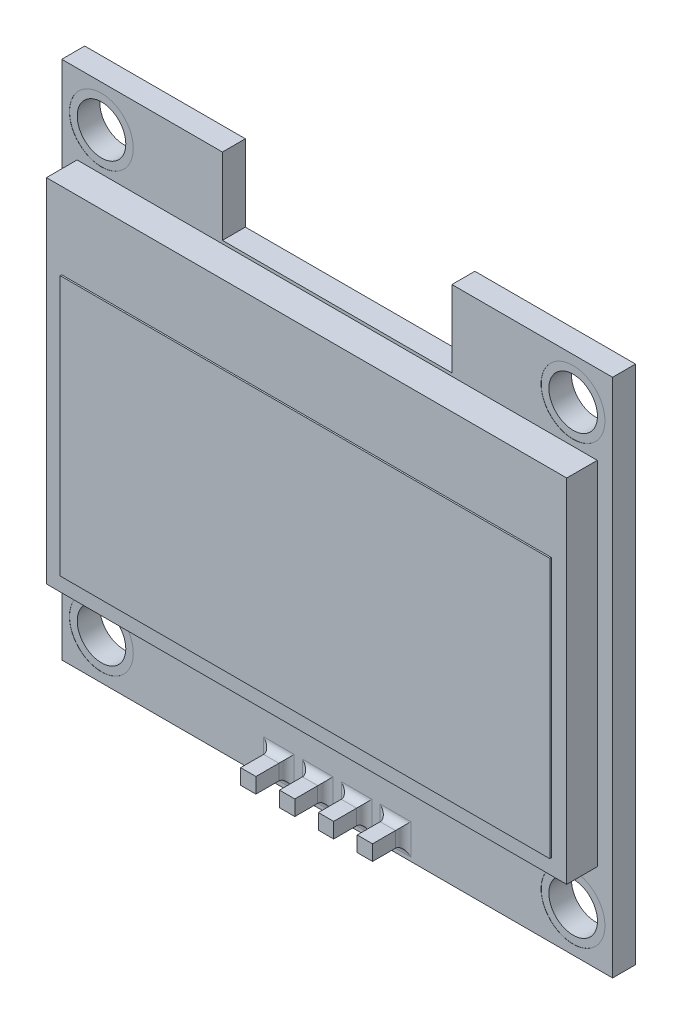
SolidWorks part; units mm, degrees
ref_plane "Alzado" through (0, 0, 0) normal (0, 0, 1) x (1, 0, 0)
ref_plane "Planta" through (0, 0, 0) normal (0, 1, 0) x (1, 0, 0)
ref_plane "Vista lateral" through (0, 0, 0) normal (1, 0, 0) x (0, 0, -1)
sketch "Croquis1" plane through (0, 0, 0) normal (0, 0, 1) x (1, 0, 0)
  line L1 (-18, 17) -> (18, 17)
  line L2 (-18, 17) -> (-18, -17)
  line L3 (-18, -17) -> (18, -17)
  line L4 (18, 17) -> (18, -17)
  line L5 (-18, 17) -> (18, -17) construction
  line L6 (-18, -17) -> (18, 17) construction
  point P0 (0, 0)
  dimension "D1" = 36
  dimension "D2" = 34
extrude "Saliente-Extruir1" add sketch "Croquis1" along normal blind 1.5
sketch "Croquis2" plane through (0, 0, 1.5) normal (0, 0, 1) x (1, 0, 0)
  line L0 (18, 17) -> (-18, 17) construction
  line L1 (-7.5, 17) -> (7.5, 17)
  line L2 (-7.5, 17) -> (-7.5, 12)
  line L3 (-7.5, 12) -> (7.5, 12)
  line L4 (7.5, 17) -> (7.5, 12)
  point P6 (0, 12)
  point P7 (0, 17)
  dimension "D1" = 15
  dimension "D2" = 5
extrude "Cortar-Extruir1" cut sketch "Croquis2" against normal blind 1.5
sketch "Croquis3" plane through (0, 0, 1.5) normal (0, 0, 1) x (1, 0, 0)
  line L0 (15.4125, 14.2875) -> (15.4125, -14.2875) construction
  line L1 (18, -17) -> (18, 17) construction
  line L2 (-15.4125, -14.2875) -> (15.4125, -14.2875) construction
  line L3 (-18, -17) -> (18, -17) construction
  circle A0 centre (-15.4125, 14.2875) radius 1.5875
  circle A1 centre (15.4125, 14.2875) radius 1.5875
  circle A2 centre (15.4125, -14.2875) radius 1.5875
  circle A3 centre (-15.4125, -14.2875) radius 1.5875
  point P8 (15.4125, 15.875)
  point P9 (17, 14.2875)
  point P10 (15.4125, -15.875)
  point P11 (-17, 14.2875)
  point P12 (15.4125, 0)
  point P13 (18, 0)
  point P14 (0, -14.2875)
  point P17 (0, -17)
  dimension "D1" = 3.175
  dimension "D2" = 31.75
  dimension "D3" = 34
extrude "Cortar-Extruir2" cut sketch "Croquis3" against normal blind 2.54
sketch "Croquis4" plane through (0, 0, 1.5) normal (0, 0, 1) x (1, 0, 0)
  line L0 (-18, -17) -> (18, -17) construction
  line L1 (-17, 11.8) -> (17, 11.8)
  line L2 (-17, 11.8) -> (-17, -11.2)
  line L3 (-17, -11.2) -> (17, -11.2)
  line L4 (17, 11.8) -> (17, -11.2)
  point P6 (0, -11.2)
  dimension "D1" = 34
  dimension "D2" = 23
  dimension "D3" = 5.8
extrude "Saliente-Extruir2" add sketch "Croquis4" along normal blind 2
sketch "Croquis5" plane through (0, 0, 3.5) normal (0, 0, 1) x (1, 0, 0)
  line L0 (-17, -11.2) -> (17, -11.2) construction
  line L1 (16, -10.2) -> (-16, -10.2)
  line L2 (16, -10.2) -> (16, 6.8)
  line L3 (16, 6.8) -> (-16, 6.8)
  line L4 (-16, -10.2) -> (-16, 6.8)
  line L5 (17, -11.2) -> (17, 11.8) construction
  line L6 (-17, 11.8) -> (-17, -11.2) construction
  line L7 (17, 11.8) -> (-17, 11.8) construction
  dimension "D1" = 1
  dimension "D2" = 1
  dimension "D3" = 1
  dimension "D4" = 5
extrude "Saliente-Extruir5" add sketch "Croquis5" along normal blind 0.1
sketch "Croquis15" plane through (0, 0, 1.5) normal (0, 0, 1) x (1, 0, 0)
  line L0 (-18, -17) -> (18, -17) construction
  line L1 (1.77, -16.25) -> (0.77, -16.25)
  line L2 (4.31, -16.25) -> (3.31, -16.25)
  line L3 (4.31, -16.25) -> (4.31, -15.25)
  line L4 (4.31, -15.25) -> (3.31, -15.25)
  line L5 (3.31, -16.25) -> (3.31, -15.25)
  line L6 (4.31, -16.25) -> (3.31, -15.25) construction
  line L7 (4.31, -15.25) -> (3.31, -16.25) construction
  line L8 (1.77, -16.25) -> (1.77, -15.25)
  line L9 (1.77, -15.25) -> (0.77, -15.25)
  line L10 (0.77, -16.25) -> (0.77, -15.25)
  line L11 (1.77, -16.25) -> (0.77, -15.25) construction
  line L12 (1.77, -15.25) -> (0.77, -16.25) construction
  line L13 (-0.77, -16.25) -> (-1.77, -16.25)
  line L14 (-0.77, -16.25) -> (-0.77, -15.25)
  line L15 (-0.77, -15.25) -> (-1.77, -15.25)
  line L16 (-1.77, -16.25) -> (-1.77, -15.25)
  line L17 (-0.77, -16.25) -> (-1.77, -15.25) construction
  line L18 (-0.77, -15.25) -> (-1.77, -16.25) construction
  line L19 (-3.31, -16.25) -> (-4.31, -16.25)
  line L20 (-3.31, -16.25) -> (-3.31, -15.25)
  line L21 (-3.31, -15.25) -> (-4.31, -15.25)
  line L22 (-4.31, -16.25) -> (-4.31, -15.25)
  line L23 (-3.31, -16.25) -> (-4.31, -15.25) construction
  line L24 (-3.31, -15.25) -> (-4.31, -16.25) construction
  line L25 (3.81, -15.75) -> (1.27, -15.75) construction
  line L26 (0.77, -15.75) -> (-0.77, -15.75) construction
  point P0 (3.81, -15.75)
  point P3 (3.81, -15.75)
  point P10 (1.27, -15.75)
  point P11 (1.27, -15.75)
  point P16 (-1.27, -15.75)
  point P17 (-1.27, -15.75)
  point P22 (-3.81, -15.75)
  point P23 (-3.81, -15.75)
  point P30 (0, -15.75)
  dimension "D1" = 1.25
  dimension "D2" = 1
  dimension "D3" = 1
  dimension "D5" = 2.54
  dimension "D4" = 4
extrude "Saliente-Extruir7" add sketch "Croquis15" along normal blind 2 and the other way blind 10
sketch "Croquis16" plane through (0, 0, 0) normal (0, 0, -1) x (-1, 0, 0)
  line L0 (4.31, -15.25) -> (4.31, -16.25) construction
  line L1 (4.31, -16.25) -> (3.31, -16.25) construction
  line L2 (1.77, -16.25) -> (0.77, -16.25) construction
  line L3 (4.81, -14.75) -> (2.81, -14.75)
  line L4 (4.81, -14.75) -> (4.81, -16.75)
  line L5 (4.81, -16.75) -> (2.81, -16.75)
  line L6 (2.81, -14.75) -> (2.81, -16.75)
  line L7 (4.81, -14.75) -> (2.81, -16.75) construction
  line L8 (4.81, -16.75) -> (2.81, -14.75) construction
  line L9 (0.27, -16.75) -> (2.27, -16.75)
  line L10 (0.27, -16.75) -> (0.27, -14.75)
  line L11 (0.27, -14.75) -> (2.27, -14.75)
  line L12 (2.27, -16.75) -> (2.27, -14.75)
  line L13 (0.27, -16.75) -> (2.27, -14.75) construction
  line L14 (0.27, -14.75) -> (2.27, -16.75) construction
  line L15 (-2.27, -16.75) -> (-0.27, -16.75)
  line L16 (-2.27, -16.75) -> (-2.27, -14.75)
  line L17 (-2.27, -14.75) -> (-0.27, -14.75)
  line L18 (-0.27, -16.75) -> (-0.27, -14.75)
  line L19 (-2.27, -16.75) -> (-0.27, -14.75) construction
  line L20 (-2.27, -14.75) -> (-0.27, -16.75) construction
  line L21 (-4.81, -16.75) -> (-2.81, -16.75)
  line L22 (-4.81, -16.75) -> (-4.81, -14.75)
  line L23 (-4.81, -14.75) -> (-2.81, -14.75)
  line L24 (-2.81, -16.75) -> (-2.81, -14.75)
  line L25 (-4.81, -16.75) -> (-2.81, -14.75) construction
  line L26 (-4.81, -14.75) -> (-2.81, -16.75) construction
  line L27 (-0.77, -16.25) -> (-1.77, -16.25) construction
  line L28 (-3.31, -16.25) -> (-4.31, -16.25) construction
  point P0 (4.31, -15.75)
  point P1 (3.81, -16.25)
  point P4 (3.81, -15.75)
  point P7 (3.81, -15.75)
  point P12 (-1.27, -15.75)
  point P14 (1.27, -15.75)
  point P22 (-3.81, -15.75)
  point P27 (-1.27, -16.25)
  point P28 (-3.81, -16.25)
  point P30 (1.27, -16.25)
  dimension "D1" = 2
  dimension "D2" = 2
extrude "Saliente-Extruir8" add sketch "Croquis16" along normal blind 2
sketch "Croquis17" plane through (0, 0, 0) normal (0, 0, -1) x (-1, 0, 0)
  line L0 (4.81, -16.75) -> (4.81, -14.75) construction
  line L1 (4.81, -16.5) -> (-4.81, -16.5)
  line L2 (4.81, -16.5) -> (4.81, -15)
  line L3 (4.81, -15) -> (-4.81, -15)
  line L4 (-4.81, -16.5) -> (-4.81, -15)
  line L5 (-4.81, -14.75) -> (-4.81, -16.75) construction
  line L6 (-4.81, -14.75) -> (-4.81, -16.75) construction
  point P8 (-4.81, -15.75)
  dimension "D1" = 1.5
extrude "Saliente-Extruir9" add sketch "Croquis17" along normal blind 2
fillet "Redondeo1" radius 0.5 16 edges at (-3.31, -15.75, 1.5) (-3.81, -16.25, 1.5) (-4.31, -15.75, 1.5) (-3.81, -15.25, 1.5) (-0.77, -15.75, 1.5) (-1.27, -15.25, 1.5) (-1.77, -15.75, 1.5) (-1.27, -16.25, 1.5) (1.27, -16.25, 1.5) (0.77, -15.75, 1.5) (1.27, -15.25, 1.5) (1.77, -15.75, 1.5) (3.31, -15.75, 1.5) (3.81, -16.25, 1.5) (4.31, -15.75, 1.5) (3.81, -15.25, 1.5)
sketch "Croquis41" plane through (0, 0, 1.5) normal (0, 0, 1) x (1, 0, 0)
  line L0 (-15.4125, 12.2) -> (-15.4125, 12.7) construction
  circle A0 centre (-15.4125, 14.2875) radius 2.0875
  circle A1 centre (15.4125, 14.2875) radius 2.0875
  circle A2 centre (15.4125, -14.2875) radius 2.0875
  circle A3 centre (-15.4125, -14.2875) radius 2.0875
  circle A4 centre (-15.4125, 14.2875) radius 1.5875 construction
  dimension "D1" = 0.5
extrude "Cortar-Extruir4" cut sketch "Croquis41" against normal blind 0.01
sketch "Croquis42" plane through (0, 0, 0) normal (0, 0, -1) x (-1, 0, 0)
  line L0 (-15.4125, 12.2) -> (-15.4125, 12.7) construction
  circle A0 centre (-15.4125, 14.2875) radius 2.0875
  circle A1 centre (15.4125, 14.2875) radius 2.0875
  circle A2 centre (15.4125, -14.2875) radius 2.0875
  circle A3 centre (-15.4125, -14.2875) radius 2.0875
  circle A4 centre (-15.4125, 14.2875) radius 1.5875 construction
  dimension "D1" = 0.5
extrude "Cortar-Extruir5" cut sketch "Croquis42" against normal blind 0.01
